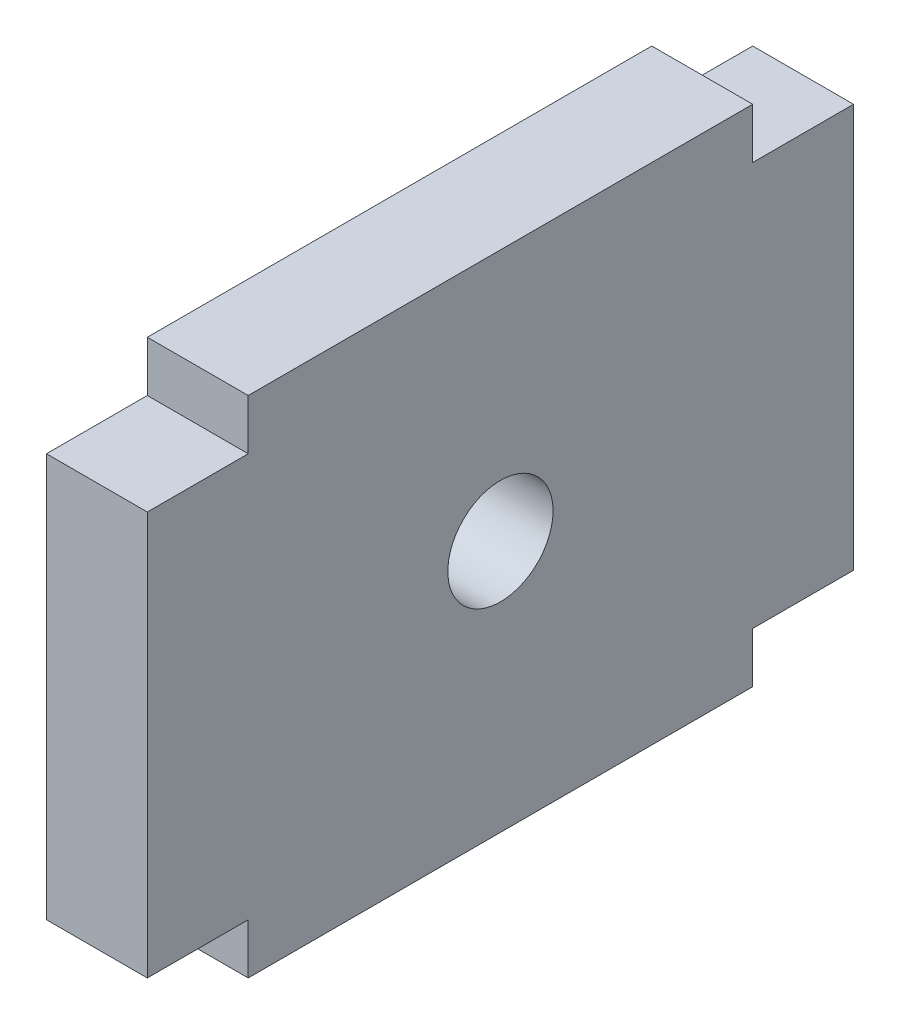
SolidWorks part; units mm, degrees
ref_plane "Přední rovina" through (0, 0, 0) normal (0, 0, 1) x (1, 0, 0)
ref_plane "Horní rovina" through (0, 0, 0) normal (0, 1, 0) x (1, 0, 0)
ref_plane "Pravá rovina" through (0, 0, 0) normal (1, 0, 0) x (0, 0, -1)
sketch "Skica1" plane through (0, 0, 0) normal (1, 0, 0) x (0, 0, -1)
  line L0 (-32.3027, 0) -> (29.782, 0) construction
  line L1 (-7.5, -7.5) -> (7.5, -7.5)
  line L2 (-7.5, -7.5) -> (-7.5, 7.5)
  line L3 (-7.5, 7.5) -> (7.5, 7.5)
  line L4 (7.5, -7.5) -> (7.5, 7.5)
  line L5 (-7.5, -7.5) -> (7.5, 7.5) construction
  line L6 (-7.5, 7.5) -> (7.5, -7.5) construction
  line L7 (0, 19.1987) -> (0, -27.6616) construction
  line L8 (-7.5, 6) -> (-10.5, -6) construction
  line L9 (7.5, -6) -> (10.5, -6)
  line L10 (7.5, -6) -> (7.5, 6)
  line L11 (7.5, 6) -> (10.5, 6)
  line L12 (10.5, -6) -> (10.5, 6)
  line L13 (7.5, -6) -> (10.5, 6) construction
  line L14 (7.5, 6) -> (10.5, -6) construction
  line L15 (-7.5, -6) -> (-10.5, 6) construction
  line L16 (-7.5, 6) -> (-10.5, 6)
  line L17 (-10.5, -6) -> (-10.5, 6)
  line L18 (-7.5, -6) -> (-10.5, -6)
  line L19 (-7.5, -6) -> (-7.5, 6)
  point P0 (0, 0)
  point P10 (9, 0)
  point P15 (-9, 0)
  dimension "D1" = 15
  dimension "D2" = 15
  dimension "D3" = 12
  dimension "D4" = 3
extrude "Přidat vysunutím1" add sketch "Skica1" along normal blind 3 contours L9 L12 L11 L4 | L1 L4 L3 L2 | L18 L2 L16 L17
sketch "Skica2" plane through (3, 0, 0) normal (1, 0, 0) x (0, 0, -1)
  circle A0 centre (0, 0) radius 1.565
  dimension "D1" = 3.13
extrude "Odebrat vysunutím1" cut sketch "Skica2" against normal blind 3
